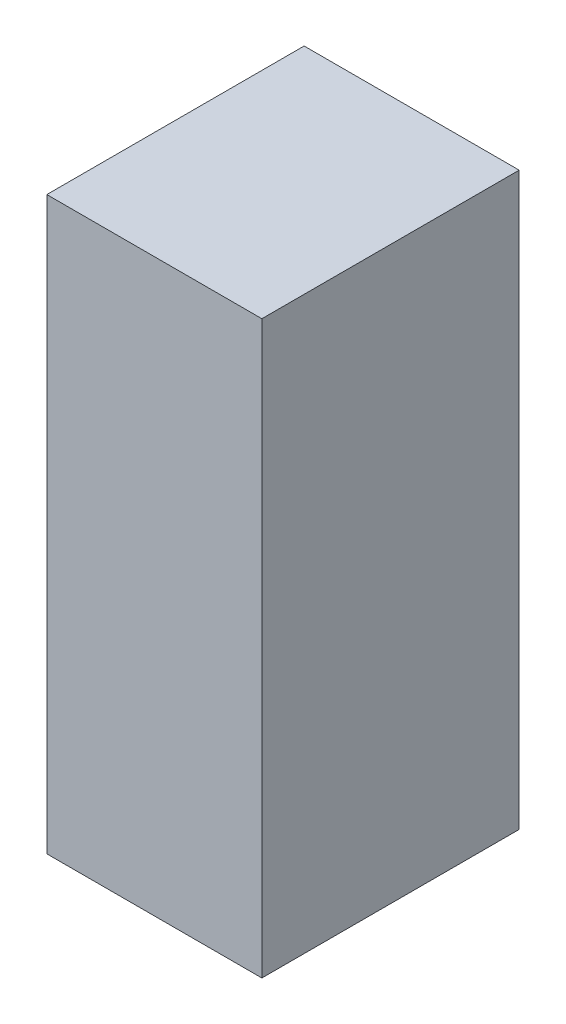
SolidWorks part; units mm, degrees
ref_plane "Front Plane" through (0, 0, 0) normal (0, 0, 1) x (1, 0, 0)
ref_plane "Top Plane" through (0, 0, 0) normal (0, 1, 0) x (1, 0, 0)
ref_plane "Right Plane" through (0, 0, 0) normal (1, 0, 0) x (0, 0, -1)
sketch "Sketch1" plane through (0, 0, 0) normal (0, 1, 0) x (1, 0, 0)
  line L1 (0, 0) -> (29, 0)
  line L2 (0, 0) -> (0, 34.7)
  line L3 (0, 34.7) -> (29, 34.7)
  line L4 (29, 0) -> (29, 34.7)
  dimension "D1" = 34.7
  dimension "D2" = 29
extrude "Boss-Extrude1" add sketch "Sketch1" along normal blind 77
